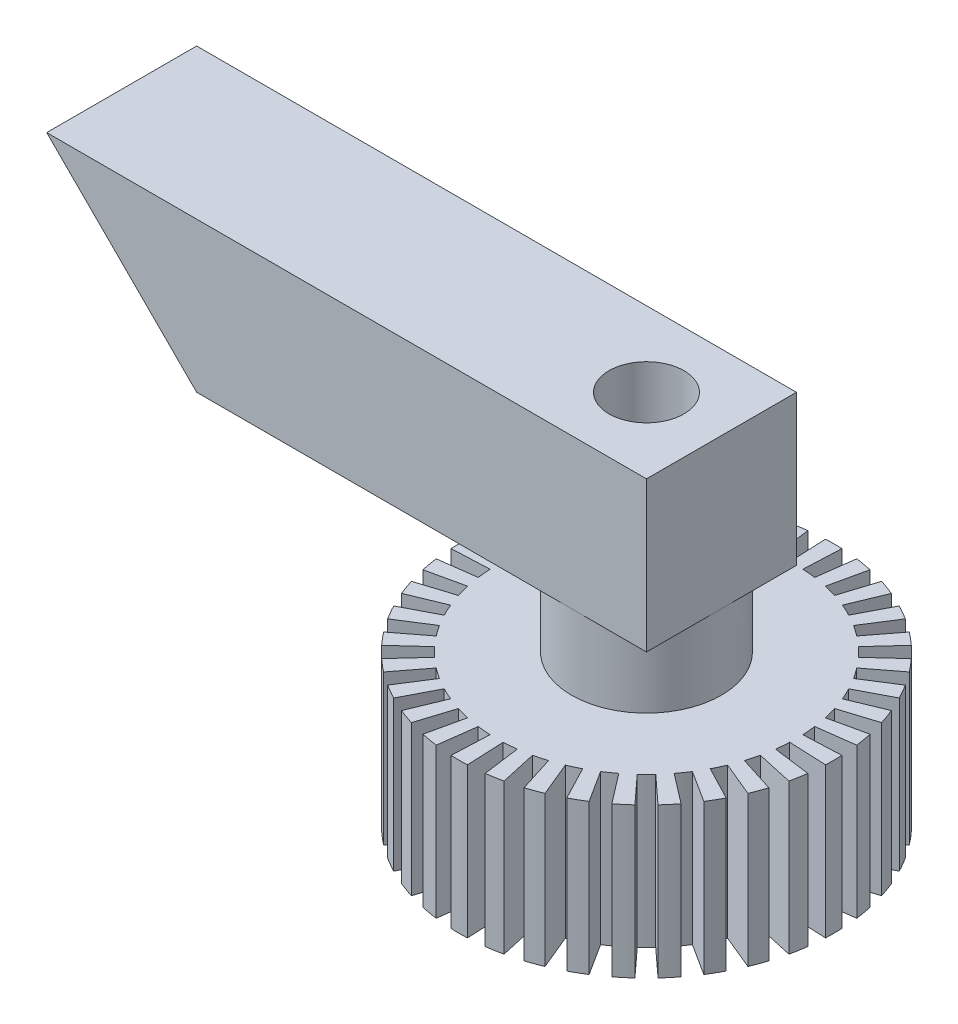
SolidWorks part; units mm, degrees
ref_plane "Front Plane" through (0, 0, 0) normal (0, 0, 1) x (1, 0, 0)
ref_plane "Top Plane" through (0, 0, 0) normal (0, 1, 0) x (1, 0, 0)
ref_plane "Right Plane" through (0, 0, 0) normal (1, 0, 0) x (0, 0, -1)
sketch "Sketch1" plane through (0, 0, 0) normal (0, 1, 0) x (1, 0, 0)
  line L0 (0, 0) -> (0, 5) construction
  line L1 (0.109, 2.4976) -> (0.0872, 1.9981)
  line L2 (-0.109, 2.4976) -> (-0.0872, 1.9981)
  line L3 (0.5411, 2.4407) -> (0.4329, 1.9526)
  line L4 (0.3263, 2.4786) -> (0.2611, 1.9829)
  line L5 (0.9567, 2.3097) -> (0.7654, 1.8478)
  line L6 (0.7518, 2.3843) -> (0.6014, 1.9074)
  line L7 (1.3432, 2.1085) -> (1.0746, 1.6868)
  line L8 (1.1544, 2.2175) -> (0.9235, 1.774)
  line L9 (1.689, 1.8432) -> (1.3512, 1.4746)
  line L10 (1.5219, 1.9834) -> (1.2175, 1.5867)
  line L11 (1.9834, 1.5219) -> (1.5867, 1.2175)
  line L12 (1.8432, 1.689) -> (1.4746, 1.3512)
  line L13 (2.2175, 1.1544) -> (1.774, 0.9235)
  line L14 (2.1085, 1.3432) -> (1.6868, 1.0746)
  line L15 (2.3843, 0.7518) -> (1.9074, 0.6014)
  line L16 (2.3097, 0.9567) -> (1.8478, 0.7654)
  line L17 (2.4786, 0.3263) -> (1.9829, 0.2611)
  line L18 (2.4407, 0.5411) -> (1.9526, 0.4329)
  line L19 (2.4976, -0.109) -> (1.9981, -0.0872)
  line L20 (2.4976, 0.109) -> (1.9981, 0.0872)
  line L21 (2.4407, -0.5411) -> (1.9526, -0.4329)
  line L22 (2.4786, -0.3263) -> (1.9829, -0.2611)
  line L23 (2.3097, -0.9567) -> (1.8478, -0.7654)
  line L24 (2.3843, -0.7518) -> (1.9074, -0.6014)
  line L25 (2.1085, -1.3432) -> (1.6868, -1.0746)
  line L26 (2.2175, -1.1544) -> (1.774, -0.9235)
  line L27 (1.8432, -1.689) -> (1.4746, -1.3512)
  line L28 (1.9834, -1.5219) -> (1.5867, -1.2175)
  line L29 (1.5219, -1.9834) -> (1.2175, -1.5867)
  line L30 (1.689, -1.8432) -> (1.3512, -1.4746)
  line L31 (1.1544, -2.2175) -> (0.9235, -1.774)
  line L32 (1.3432, -2.1085) -> (1.0746, -1.6868)
  line L33 (0.7518, -2.3843) -> (0.6014, -1.9074)
  line L34 (0.9567, -2.3097) -> (0.7654, -1.8478)
  line L35 (0.3263, -2.4786) -> (0.2611, -1.9829)
  line L36 (0.5411, -2.4407) -> (0.4329, -1.9526)
  line L37 (-0.109, -2.4976) -> (-0.0872, -1.9981)
  line L38 (0.109, -2.4976) -> (0.0872, -1.9981)
  line L39 (-0.5411, -2.4407) -> (-0.4329, -1.9526)
  line L40 (-0.3263, -2.4786) -> (-0.2611, -1.9829)
  line L41 (-0.9567, -2.3097) -> (-0.7654, -1.8478)
  line L42 (-0.7518, -2.3843) -> (-0.6014, -1.9074)
  line L43 (-1.3432, -2.1085) -> (-1.0746, -1.6868)
  line L44 (-1.1544, -2.2175) -> (-0.9235, -1.774)
  line L45 (-1.689, -1.8432) -> (-1.3512, -1.4746)
  line L46 (-1.5219, -1.9834) -> (-1.2175, -1.5867)
  line L47 (-1.9834, -1.5219) -> (-1.5867, -1.2175)
  line L48 (-1.8432, -1.689) -> (-1.4746, -1.3512)
  line L49 (-2.2175, -1.1544) -> (-1.774, -0.9235)
  line L50 (-2.1085, -1.3432) -> (-1.6868, -1.0746)
  line L51 (-2.3843, -0.7518) -> (-1.9074, -0.6014)
  line L52 (-2.3097, -0.9567) -> (-1.8478, -0.7654)
  line L53 (-2.4786, -0.3263) -> (-1.9829, -0.2611)
  line L54 (-2.4407, -0.5411) -> (-1.9526, -0.4329)
  line L55 (-2.4976, 0.109) -> (-1.9981, 0.0872)
  line L56 (-2.4976, -0.109) -> (-1.9981, -0.0872)
  line L57 (-2.4407, 0.5411) -> (-1.9526, 0.4329)
  line L58 (-2.4786, 0.3263) -> (-1.9829, 0.2611)
  line L59 (-2.3097, 0.9567) -> (-1.8478, 0.7654)
  line L60 (-2.3843, 0.7518) -> (-1.9074, 0.6014)
  line L61 (-2.1085, 1.3432) -> (-1.6868, 1.0746)
  line L62 (-2.2175, 1.1544) -> (-1.774, 0.9235)
  line L63 (-1.8432, 1.689) -> (-1.4746, 1.3512)
  line L64 (-1.9834, 1.5219) -> (-1.5867, 1.2175)
  line L65 (-1.5219, 1.9834) -> (-1.2175, 1.5867)
  line L66 (-1.689, 1.8432) -> (-1.3512, 1.4746)
  line L67 (-1.1544, 2.2175) -> (-0.9235, 1.774)
  line L68 (-1.3432, 2.1085) -> (-1.0746, 1.6868)
  line L69 (-0.7518, 2.3843) -> (-0.6014, 1.9074)
  line L70 (-0.9567, 2.3097) -> (-0.7654, 1.8478)
  line L71 (-0.3263, 2.4786) -> (-0.2611, 1.9829)
  line L72 (-0.5411, 2.4407) -> (-0.4329, 1.9526)
  arc A0 (0.109, 2.4976) -> (-0.109, 2.4976) centre (0, 0) ccw
  arc A1 (-0.0872, 1.9981) -> (-0.2611, 1.9829) centre (0, 0) ccw
  arc A2 (0.5411, 2.4407) -> (0.3263, 2.4786) centre (0, 0) ccw
  arc A3 (0.2611, 1.9829) -> (0.0872, 1.9981) centre (0, 0) ccw
  arc A4 (0.9567, 2.3097) -> (0.7518, 2.3843) centre (0, 0) ccw
  arc A5 (0.6014, 1.9074) -> (0.4329, 1.9526) centre (0, 0) ccw
  arc A6 (1.3432, 2.1085) -> (1.1544, 2.2175) centre (0, 0) ccw
  arc A7 (0.9235, 1.774) -> (0.7654, 1.8478) centre (0, 0) ccw
  arc A8 (1.689, 1.8432) -> (1.5219, 1.9834) centre (0, 0) ccw
  arc A9 (1.2175, 1.5867) -> (1.0746, 1.6868) centre (0, 0) ccw
  arc A10 (1.9834, 1.5219) -> (1.8432, 1.689) centre (0, 0) ccw
  arc A11 (1.4746, 1.3512) -> (1.3512, 1.4746) centre (0, 0) ccw
  arc A12 (2.2175, 1.1544) -> (2.1085, 1.3432) centre (0, 0) ccw
  arc A13 (1.6868, 1.0746) -> (1.5867, 1.2175) centre (0, 0) ccw
  arc A14 (2.3843, 0.7518) -> (2.3097, 0.9567) centre (0, 0) ccw
  arc A15 (1.8478, 0.7654) -> (1.774, 0.9235) centre (0, 0) ccw
  arc A16 (2.4786, 0.3263) -> (2.4407, 0.5411) centre (0, 0) ccw
  arc A17 (1.9526, 0.4329) -> (1.9074, 0.6014) centre (0, 0) ccw
  arc A18 (2.4976, -0.109) -> (2.4976, 0.109) centre (0, 0) ccw
  arc A19 (1.9981, 0.0872) -> (1.9829, 0.2611) centre (0, 0) ccw
  arc A20 (2.4407, -0.5411) -> (2.4786, -0.3263) centre (0, 0) ccw
  arc A21 (1.9829, -0.2611) -> (1.9981, -0.0872) centre (0, 0) ccw
  arc A22 (2.3097, -0.9567) -> (2.3843, -0.7518) centre (0, 0) ccw
  arc A23 (1.9074, -0.6014) -> (1.9526, -0.4329) centre (0, 0) ccw
  arc A24 (2.1085, -1.3432) -> (2.2175, -1.1544) centre (0, 0) ccw
  arc A25 (1.774, -0.9235) -> (1.8478, -0.7654) centre (0, 0) ccw
  arc A26 (1.8432, -1.689) -> (1.9834, -1.5219) centre (0, 0) ccw
  arc A27 (1.5867, -1.2175) -> (1.6868, -1.0746) centre (0, 0) ccw
  arc A28 (1.5219, -1.9834) -> (1.689, -1.8432) centre (0, 0) ccw
  arc A29 (1.3512, -1.4746) -> (1.4746, -1.3512) centre (0, 0) ccw
  arc A30 (1.1544, -2.2175) -> (1.3432, -2.1085) centre (0, 0) ccw
  arc A31 (1.0746, -1.6868) -> (1.2175, -1.5867) centre (0, 0) ccw
  arc A32 (0.7518, -2.3843) -> (0.9567, -2.3097) centre (0, 0) ccw
  arc A33 (0.7654, -1.8478) -> (0.9235, -1.774) centre (0, 0) ccw
  arc A34 (0.3263, -2.4786) -> (0.5411, -2.4407) centre (0, 0) ccw
  arc A35 (0.4329, -1.9526) -> (0.6014, -1.9074) centre (0, 0) ccw
  arc A36 (-0.109, -2.4976) -> (0.109, -2.4976) centre (0, 0) ccw
  arc A37 (0.0872, -1.9981) -> (0.2611, -1.9829) centre (0, 0) ccw
  arc A38 (-0.5411, -2.4407) -> (-0.3263, -2.4786) centre (0, 0) ccw
  arc A39 (-0.2611, -1.9829) -> (-0.0872, -1.9981) centre (0, 0) ccw
  arc A40 (-0.9567, -2.3097) -> (-0.7518, -2.3843) centre (0, 0) ccw
  arc A41 (-0.6014, -1.9074) -> (-0.4329, -1.9526) centre (0, 0) ccw
  arc A42 (-1.3432, -2.1085) -> (-1.1544, -2.2175) centre (0, 0) ccw
  arc A43 (-0.9235, -1.774) -> (-0.7654, -1.8478) centre (0, 0) ccw
  arc A44 (-1.689, -1.8432) -> (-1.5219, -1.9834) centre (0, 0) ccw
  arc A45 (-1.2175, -1.5867) -> (-1.0746, -1.6868) centre (0, 0) ccw
  arc A46 (-1.9834, -1.5219) -> (-1.8432, -1.689) centre (0, 0) ccw
  arc A47 (-1.4746, -1.3512) -> (-1.3512, -1.4746) centre (0, 0) ccw
  arc A48 (-2.2175, -1.1544) -> (-2.1085, -1.3432) centre (0, 0) ccw
  arc A49 (-1.6868, -1.0746) -> (-1.5867, -1.2175) centre (0, 0) ccw
  arc A50 (-2.3843, -0.7518) -> (-2.3097, -0.9567) centre (0, 0) ccw
  arc A51 (-1.8478, -0.7654) -> (-1.774, -0.9235) centre (0, 0) ccw
  arc A52 (-2.4786, -0.3263) -> (-2.4407, -0.5411) centre (0, 0) ccw
  arc A53 (-1.9526, -0.4329) -> (-1.9074, -0.6014) centre (0, 0) ccw
  arc A54 (-2.4976, 0.109) -> (-2.4976, -0.109) centre (0, 0) ccw
  arc A55 (-1.9981, -0.0872) -> (-1.9829, -0.2611) centre (0, 0) ccw
  arc A56 (-2.4407, 0.5411) -> (-2.4786, 0.3263) centre (0, 0) ccw
  arc A57 (-1.9829, 0.2611) -> (-1.9981, 0.0872) centre (0, 0) ccw
  arc A58 (-2.3097, 0.9567) -> (-2.3843, 0.7518) centre (0, 0) ccw
  arc A59 (-1.9074, 0.6014) -> (-1.9526, 0.4329) centre (0, 0) ccw
  arc A60 (-2.1085, 1.3432) -> (-2.2175, 1.1544) centre (0, 0) ccw
  arc A61 (-1.774, 0.9235) -> (-1.8478, 0.7654) centre (0, 0) ccw
  arc A62 (-1.8432, 1.689) -> (-1.9834, 1.5219) centre (0, 0) ccw
  arc A63 (-1.5867, 1.2175) -> (-1.6868, 1.0746) centre (0, 0) ccw
  arc A64 (-1.5219, 1.9834) -> (-1.689, 1.8432) centre (0, 0) ccw
  arc A65 (-1.3512, 1.4746) -> (-1.4746, 1.3512) centre (0, 0) ccw
  arc A66 (-1.1544, 2.2175) -> (-1.3432, 2.1085) centre (0, 0) ccw
  arc A67 (-1.0746, 1.6868) -> (-1.2175, 1.5867) centre (0, 0) ccw
  arc A68 (-0.7518, 2.3843) -> (-0.9567, 2.3097) centre (0, 0) ccw
  arc A69 (-0.7654, 1.8478) -> (-0.9235, 1.774) centre (0, 0) ccw
  arc A70 (-0.3263, 2.4786) -> (-0.5411, 2.4407) centre (0, 0) ccw
  arc A71 (-0.4329, 1.9526) -> (-0.6014, 1.9074) centre (0, 0) ccw
  point P186 (0, 0)
  dimension "D2" = 36
  dimension "D3" = 2.5
  dimension "D1" = 0.5
extrude "Boss-Extrude1" add sketch "Sketch1" along normal blind 2
sketch "Sketch2" plane through (0, 2, 0) normal (0, 1, 0) x (1, 0, 0)
  circle A0 centre (0, 0) radius 1
extrude "Boss-Extrude2" add sketch "Sketch2" along normal blind 1
sketch "Sketch3" plane through (0, 3, 0) normal (0, 1, 0) x (1, 0, 0)
  line L1 (1, 1) -> (-7, 1)
  line L2 (1, 1) -> (1, -1)
  line L3 (1, -1) -> (-7, -1)
  line L4 (-7, 1) -> (-7, -1)
  circle A0 centre (0, 0) radius 1 construction
  circle A1 centre (0, 0) radius 1 construction
  dimension "D1" = 8
  dimension "D2" = 2
  dimension "D3" = 1
  dimension "D4" = 1
extrude "Boss-Extrude3" add sketch "Sketch3" along normal blind 2
sketch "Sketch4" plane through (0, 5, 0) normal (0, 1, 0) x (1, 0, 0)
  circle A0 centre (0, 0) radius 0.5
extrude "Cut-Extrude1" cut sketch "Sketch4" against normal through all
sketch "Sketch5" plane through (0, 0, -1) normal (0, 0, -1) x (-1, 0, 0)
  line L0 (7, 5) -> (5, 3)
  line L1 (0, 3) -> (7, 3) construction
  line L2 (5, 3) -> (7, 3)
  line L3 (7, 3) -> (7, 5)
extrude "Cut-Extrude2" cut sketch "Sketch5" against normal through all
